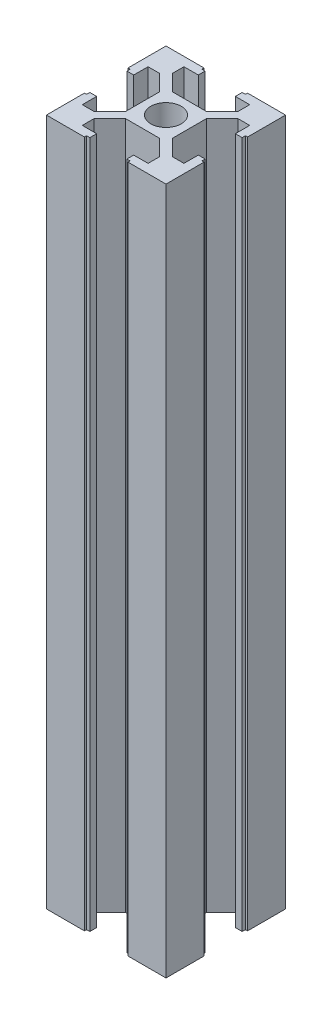
SolidWorks part; units mm, degrees
material "AISI 304"
ref_plane "前视基准面" through (0, 0, 0) normal (0, 0, 1) x (1, 0, 0)
ref_plane "上视基准面" through (0, 0, 0) normal (0, 1, 0) x (1, 0, 0)
ref_plane "右视基准面" through (0, 0, 0) normal (1, 0, 0) x (0, 0, -1)
sketch "Sketch1" plane through (0, 0, 0) normal (0, 1, 0) x (1, 0, 0)
  line L0 (-3.9, 2.8393) -> (-6.5607, 5.5)
  line L1 (-10, 10) -> (-3.65, 10)
  line L2 (-10, 10) -> (-10, 3.65)
  line L3 (-10, -10) -> (-3.65, -10)
  line L4 (10, 10) -> (10, -10)
  line L5 (0, -10) -> (0, 10) construction
  line L6 (-10, 0) -> (10, 0) construction
  line L7 (-2.8393, 3.9) -> (2.8393, 3.9)
  line L8 (-3.9, 2.8393) -> (-3.9, -2.8393)
  line L9 (-2.8393, -3.9) -> (2.8393, -3.9)
  line L10 (3.9, 2.8393) -> (3.9, -2.8393)
  line L11 (0, -3.9) -> (0, 3.9) construction
  line L12 (-3.9, 0) -> (3.9, 0) construction
  line L13 (-6.5607, 5.5) -> (-8.5, 5.5)
  line L14 (-8.5, 5.5) -> (-8.5, 3.1)
  line L15 (-8.5, 3.1) -> (-9.6397, 3.1)
  line L16 (-9.6397, 3.1) -> (-9.6397, 3.65)
  line L17 (-9.6397, 3.65) -> (-10, 3.65)
  line L18 (0, 0) -> (-10, 10) construction
  line L19 (-3.65, 9.6397) -> (-3.65, 10)
  line L20 (-3.1, 9.6397) -> (-3.65, 9.6397)
  line L21 (-3.1, 8.5) -> (-3.1, 9.6397)
  line L22 (-5.5, 8.5) -> (-3.1, 8.5)
  line L23 (-5.5, 6.5607) -> (-5.5, 8.5)
  line L24 (-2.8393, 3.9) -> (-5.5, 6.5607)
  line L25 (2.8393, 3.9) -> (5.5, 6.5607)
  line L26 (5.5, 6.5607) -> (5.5, 8.5)
  line L27 (5.5, 8.5) -> (3.1, 8.5)
  line L28 (3.1, 8.5) -> (3.1, 9.6397)
  line L29 (3.1, 9.6397) -> (3.65, 9.6397)
  line L30 (3.65, 9.6397) -> (3.65, 10)
  line L31 (9.6397, 3.65) -> (10, 3.65)
  line L32 (9.6397, 3.1) -> (9.6397, 3.65)
  line L33 (8.5, 3.1) -> (9.6397, 3.1)
  line L34 (8.5, 5.5) -> (8.5, 3.1)
  line L35 (6.5607, 5.5) -> (8.5, 5.5)
  line L36 (3.9, 2.8393) -> (6.5607, 5.5)
  line L37 (3.9, -2.8393) -> (6.5607, -5.5)
  line L38 (6.5607, -5.5) -> (8.5, -5.5)
  line L39 (8.5, -5.5) -> (8.5, -3.1)
  line L40 (8.5, -3.1) -> (9.6397, -3.1)
  line L41 (9.6397, -3.1) -> (9.6397, -3.65)
  line L42 (9.6397, -3.65) -> (10, -3.65)
  line L43 (3.65, -9.6397) -> (3.65, -10)
  line L44 (3.1, -9.6397) -> (3.65, -9.6397)
  line L45 (3.1, -8.5) -> (3.1, -9.6397)
  line L46 (5.5, -8.5) -> (3.1, -8.5)
  line L47 (5.5, -6.5607) -> (5.5, -8.5)
  line L48 (2.8393, -3.9) -> (5.5, -6.5607)
  line L49 (-2.8393, -3.9) -> (-5.5, -6.5607)
  line L50 (-5.5, -6.5607) -> (-5.5, -8.5)
  line L51 (-5.5, -8.5) -> (-3.1, -8.5)
  line L52 (-3.1, -8.5) -> (-3.1, -9.6397)
  line L53 (-3.1, -9.6397) -> (-3.65, -9.6397)
  line L54 (-3.65, -9.6397) -> (-3.65, -10)
  line L55 (-9.6397, -3.65) -> (-10, -3.65)
  line L56 (-9.6397, -3.1) -> (-9.6397, -3.65)
  line L57 (-8.5, -3.1) -> (-9.6397, -3.1)
  line L58 (-8.5, -5.5) -> (-8.5, -3.1)
  line L59 (-6.5607, -5.5) -> (-8.5, -5.5)
  line L60 (-3.9, -2.8393) -> (-6.5607, -5.5)
  line L61 (-3.9, 3.9) -> (-3.9, 2.8393) construction
  line L62 (-3.9, -2.8393) -> (-3.9, -3.9) construction
  line L63 (3.9, -2.8393) -> (3.9, -3.9) construction
  line L64 (3.9, 3.9) -> (3.9, 2.8393) construction
  line L65 (-3.9, 3.9) -> (-2.8393, 3.9) construction
  line L66 (2.8393, 3.9) -> (3.9, 3.9) construction
  line L67 (-3.9, -3.9) -> (-2.8393, -3.9) construction
  line L68 (2.8393, -3.9) -> (3.9, -3.9) construction
  line L69 (-3.65, 10) -> (0, 10) construction
  line L70 (3.65, 10) -> (10, 10)
  line L71 (0, 10) -> (3.65, 10) construction
  line L72 (-10, 3.65) -> (-10, 0) construction
  line L73 (-10, -3.65) -> (-10, -10)
  line L74 (-10, 0) -> (-10, -3.65) construction
  line L75 (-3.65, -10) -> (0, -10) construction
  line L76 (3.65, -10) -> (10, -10)
  line L77 (0, -10) -> (3.65, -10) construction
  circle A0 centre (0, 0) radius 2.55
  point P0 (0, 0)
  dimension "D3" = 5.1
  dimension "D1" = 20
  dimension "D2" = 20
  dimension "D4" = 6.1
  dimension "D5" = 6.2
  dimension "D6" = 1.5
  dimension "D7" = 7.3
  dimension "D8" = 5.5
  dimension "D9" = 1.5
extrude "Boss-Extrude1" add sketch "Sketch1" along normal mid plane 115 contours L43 L76 L4 L42 L41 L40 L39 L38 L37 L10 L36 L35 L34 L33 L32 L31 L70 L30 L29 L28 L27 L26 L25 L7 L24 L23 L22 L21 L20 L19 L1 L2 L17 L16 L15 L14 L13 L0 L8 L60 L59 L58 L57 L56 L55 L73 L3 L54 L53 L52
